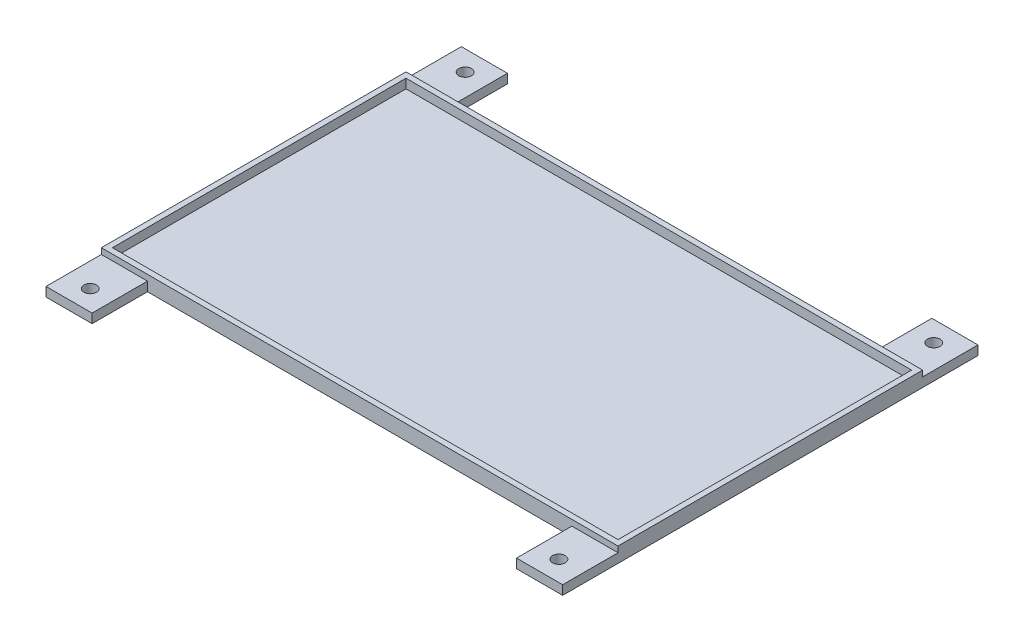
SolidWorks part; units mm, degrees
ref_plane "Front Plane" through (0, 0, 0) normal (0, 0, 1) x (1, 0, 0)
ref_plane "Top Plane" through (0, 0, 0) normal (0, 1, 0) x (1, 0, 0)
ref_plane "Right Plane" through (0, 0, 0) normal (1, 0, 0) x (0, 0, -1)
sketch "Sketch1" plane through (0, 0, 0) normal (0, 1, 0) x (1, 0, 0)
  line L1 (-140, -82.55) -> (140, -82.55)
  line L2 (-140, -82.55) -> (-140, 82.55)
  line L3 (-140, 82.55) -> (140, 82.55)
  line L4 (140, -82.55) -> (140, 82.55)
  line L5 (-140, -82.55) -> (140, 82.55) construction
  line L6 (-140, 82.55) -> (140, -82.55) construction
  point P0 (0, 0)
  dimension "D1" = 165.1
  dimension "D2" = 280
extrude "Boss-Extrude1" add sketch "Sketch1" along normal blind 3.175
sketch "Sketch2" plane through (0, 3.175, 0) normal (0, 1, 0) x (1, 0, 0)
  line L0 (137, -79.55) -> (137, 79.55)
  line L1 (137, 79.55) -> (-137, 79.55)
  line L2 (-137, 79.55) -> (-137, -79.55)
  line L3 (-137, -79.55) -> (137, -79.55)
  line L4 (140, -82.55) -> (140, 82.55)
  line L5 (140, 82.55) -> (-140, 82.55)
  line L6 (-140, 82.55) -> (-140, -82.55)
  line L7 (-140, -82.55) -> (140, -82.55)
  line L8 (140, -82.55) -> (140, 82.55)
  line L9 (140, 82.55) -> (-140, 82.55)
  line L10 (-140, 82.55) -> (-140, -82.55)
  line L11 (-140, -82.55) -> (140, -82.55)
  dimension "D1" = 0
  dimension "D2" = 3
extrude "Boss-Extrude2" add sketch "Sketch2" along normal blind 5
sketch "Sketch3" plane through (0, 0, 0) normal (0, 1, 0) x (1, 0, 0)
  line L0 (-127, 101.6) -> (127, 101.6) construction
  line L1 (-140, 82.55) -> (-115, 82.55)
  line L2 (-140, 82.55) -> (-140, 112.55)
  line L3 (-140, 112.55) -> (-115, 112.55)
  line L4 (-115, 82.55) -> (-115, 112.55)
  line L5 (140, 82.55) -> (115, 82.55)
  line L6 (140, 82.55) -> (140, 112.55)
  line L7 (140, 112.55) -> (115, 112.55)
  line L8 (115, 82.55) -> (115, 112.55)
  line L9 (-140, -82.55) -> (-115, -82.55)
  line L10 (-140, -82.55) -> (-140, -112.55)
  line L11 (-140, -112.55) -> (-115, -112.55)
  line L12 (-115, -82.55) -> (-115, -112.55)
  line L13 (140, -82.55) -> (115, -82.55)
  line L14 (140, -82.55) -> (140, -112.55)
  line L15 (140, -112.55) -> (115, -112.55)
  line L16 (115, -82.55) -> (115, -112.55)
  line L17 (127, 101.6) -> (127, -101.6) construction
  line L18 (127, -101.6) -> (-127, -101.6) construction
  line L19 (-127, -101.6) -> (-127, 101.6) construction
  line L20 (-140, 0) -> (140, 0) construction
  line L21 (-140, 82.55) -> (-140, -82.55) construction
  line L22 (140, -82.55) -> (140, 82.55) construction
  line L23 (0, 101.6) -> (0, -101.6) construction
  circle A0 centre (-127, 101.6) radius 3.429
  circle A1 centre (127, 101.6) radius 3.429
  circle A2 centre (127, -101.6) radius 3.429
  circle A3 centre (-127, -101.6) radius 3.429
  point P28 (-127.5, -82.55)
  point P29 (-115, -97.55)
  point P30 (127.5, -82.55)
  point P31 (-115, 97.55)
  dimension "D5" = 6.858
  dimension "D1" = 25
  dimension "D2" = 25
  dimension "D3" = 30
  dimension "D4" = 30
  dimension "D6" = 203.2
  dimension "D7" = 254
extrude "Boss-Extrude3" add sketch "Sketch3" along normal blind 5
equation "\"D2@Sketch3\"=\"D1@Sketch3\""
equation "\"D4@Sketch3\"=\"D3@Sketch3\""
